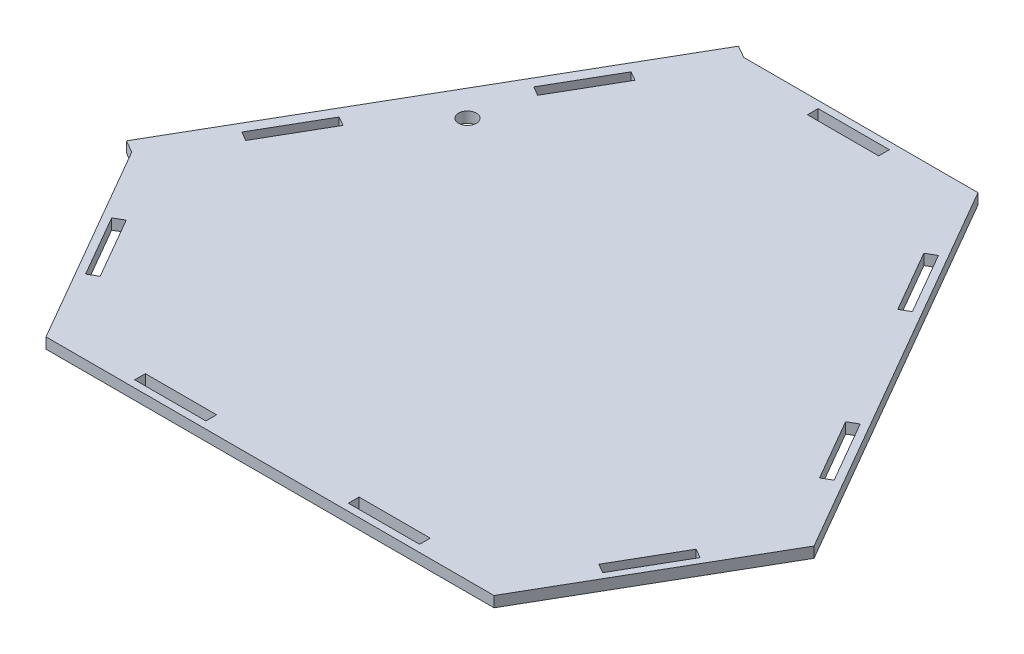
SolidWorks part; units mm, degrees
material "Acrylic (Medium-high impact)"
ref_plane "Front Plane" through (0, 0, 0) normal (0, 0, 1) x (1, 0, 0)
ref_plane "Top Plane" through (0, 0, 0) normal (0, 1, 0) x (1, 0, 0)
ref_plane "Right Plane" through (0, 0, 0) normal (1, 0, 0) x (0, 0, -1)
sketch "Sketch4" plane through (0, 0, 0) normal (0, 1, 0) x (1, 0, 0)
  line L0 (-30, 86.6025) -> (30, 86.6025)
  line L1 (0, 138.5641) -> (-120, -69.282) construction
  line L2 (-120, -69.282) -> (120, -69.282) construction
  line L3 (120, -69.282) -> (0, 138.5641) construction
  line L4 (-120, -69.282) -> (0, 0) construction
  line L5 (60, -69.282) -> (90, -17.3205)
  line L6 (0, 0) -> (0, 138.5641) construction
  line L7 (-60, -69.282) -> (-90, -17.3205)
  line L8 (-30, 86.6025) -> (-90, -17.3205)
  line L9 (-60, -69.282) -> (60, -69.282)
  line L10 (90, -17.3205) -> (30, 86.6025)
  line L11 (-32.8868, 91.6025) -> (32.8868, 91.6025)
  line L12 (95.7735, -17.3205) -> (32.8868, 91.6025)
  line L13 (62.8868, -74.282) -> (95.7735, -17.3205)
  line L14 (-62.8868, -74.282) -> (62.8868, -74.282)
  line L15 (-62.8868, -74.282) -> (-95.7735, -17.3205)
  line L16 (-32.8868, 91.6025) -> (-95.7735, -17.3205)
  line L17 (-94.3301, -14.8205) -> (-99.5263, -11.8205)
  line L18 (-94.3301, -14.8205) -> (-34.3058, 89.1447)
  line L19 (-99.5263, -11.8205) -> (-39.5019, 92.1447)
  line L20 (-34.3058, 89.1447) -> (-39.5019, 92.1447)
  line L21 (-92.5981, -15.8205) -> (-95.1962, -14.3205) construction
  circle A0 centre (0, 0) radius 69.282 construction
  dimension "D1" = 60
  dimension "D2" = 120
  dimension "D4" = 6
  dimension "D3" = 5
extrude "Boss-Extrude1" add sketch "Sketch4" against normal blind 3 contours L11 L12 L13 L14 L15 L16
sketch "Sketch5" plane through (0, 0, 0) normal (0, 1, 0) x (1, 0, 0)
  line L0 (-95.7735, -17.3205) -> (-32.8868, 91.6025)
  line L1 (-95.7735, -17.3205) -> (-99.2376, -15.3205)
  line L2 (-32.8868, 91.6025) -> (-36.3509, 93.6025)
  line L3 (-99.2376, -15.3205) -> (-36.3509, 93.6025)
  dimension "D1" = 4
extrude "Boss-Extrude2" add sketch "Sketch5" against normal through all
sketch "Sketch6" plane through (0, 0, 0) normal (0, 1, 0) x (1, 0, 0)
  line L0 (-67.7942, 39.141) -> (88.9811, -51.3732) construction
  line L1 (-36.3509, 93.6025) -> (-99.2376, -15.3205) construction
  circle A0 centre (-56.884, 38.0381) radius 2.5
  dimension "D1" = 5
  dimension "D2" = 10
  dimension "D3" = 4.5
extrude "Cut-Extrude1" cut sketch "Sketch6" against normal through all
sketch "Sketch7" plane through (0, 0, 0) normal (0, 1, 0) x (1, 0, 0)
  line L0 (-33.1171, 89.6025) -> (57.2276, 89.6025) construction
  line L1 (-70, 17.3205) -> (-80, 0) [skipped]
  line L2 (-32.8868, 91.6025) -> (32.8868, 91.6025) construction
  line L3 (-10, 89.6025) -> (10, 89.6025)
  line L4 (-10, 89.6025) -> (-10, 86.6025)
  line L5 (-10, 86.6025) -> (10, 86.6025)
  line L6 (10, 89.6025) -> (10, 86.6025)
  line L7 (0, 91.6025) -> (0, 31.1877) construction
  line L8 (-62.8868, -72.282) -> (98.3225, -72.282) construction
  line L9 (-62.8868, -74.282) -> (62.8868, -74.282) construction
  line L10 (-72.5981, 18.8205) -> (-82.5981, 1.5) [skipped]
  line L11 (-82.5981, 1.5) -> (-80, 0) [skipped]
  line L12 (-40, -72.282) -> (-20, -72.282)
  line L13 (-40, -72.282) -> (-40, -69.282)
  line L14 (-72.5981, 18.8205) -> (-70, 17.3205) [skipped]
  line L15 (-40, -69.282) -> (-20, -69.282)
  line L16 (-20, -72.282) -> (-20, -69.282)
  line L17 (20, -72.282) -> (40, -72.282)
  line L18 (20, -72.282) -> (20, -69.282)
  line L19 (20, -69.282) -> (40, -69.282)
  line L20 (40, -72.282) -> (40, -69.282)
  line L21 (-52.5981, 53.4615) -> (-50, 51.9615) [skipped]
  line L22 (-42.5981, 70.782) -> (-40, 69.282) [skipped]
  line L23 (-40, 69.282) -> (-50, 51.9615) [skipped]
  line L24 (-42.5981, 70.782) -> (-52.5981, 53.4615) [skipped]
  line L25 (50, 51.9615) -> (40, 69.282)
  line L26 (52.5981, 53.4615) -> (42.5981, 70.782)
  line L27 (42.5981, 70.782) -> (40, 69.282)
  line L28 (52.5981, 53.4615) -> (50, 51.9615)
  line L29 (72.5981, 18.8205) -> (70, 17.3205)
  line L30 (82.5981, 1.5) -> (80, 0)
  line L31 (80, 0) -> (70, 17.3205)
  line L32 (82.5981, 1.5) -> (72.5981, 18.8205)
  line L33 (80, -34.641) -> (70, -51.9615)
  line L34 (82.5981, -36.141) -> (72.5981, -53.4615)
  line L35 (72.5981, -53.4615) -> (70, -51.9615)
  line L36 (82.5981, -36.141) -> (80, -34.641)
  line L37 (-70, -51.9615) -> (-80, -34.641)
  line L38 (-72.5981, -53.4615) -> (-82.5981, -36.141)
  line L39 (-82.5981, -36.141) -> (-80, -34.641)
  line L40 (-72.5981, -53.4615) -> (-70, -51.9615)
  line L41 (-36.3509, 93.6025) -> (-99.2376, -15.3205) construction
  line L42 (-36.3509, 93.6025) -> (-33.7528, 92.1025) construction
  line L43 (-99.2376, -15.3205) -> (-96.6395, -16.8205) construction
  line L44 (-33.7528, 92.1025) -> (-96.6395, -16.8205) construction
  line L45 (-45.1962, 72.282) -> (-55.1962, 54.9615)
  line L46 (-45.1962, 72.282) -> (-42.5981, 70.782)
  line L47 (-55.1962, 54.9615) -> (-52.5981, 53.4615)
  line L48 (-42.5981, 70.782) -> (-52.5981, 53.4615)
  line L49 (-75.1962, 20.3205) -> (-85.1962, 3)
  line L50 (-75.1962, 20.3205) -> (-72.5981, 18.8205)
  line L51 (-85.1962, 3) -> (-82.5981, 1.5)
  line L52 (-72.5981, 18.8205) -> (-82.5981, 1.5)
  line L53 (0, -74.282) -> (0, -25.4234) construction
  line L54 (-67.7942, 39.141) -> (-18.2487, 10.5359) construction
  circle A0 centre (0, 0) radius 16.4887 construction
  point P46 (0, 0)
  point P55 (0, 0)
  dimension "D1" = 2
  dimension "D2" = 20
  dimension "D3" = 3
  dimension "D4" = 2
  dimension "D5" = 10
  dimension "D6" = 3
  dimension "D7" = 20
  dimension "D8" = 20
  dimension "D9" = 3
  dimension "D10" = 40
  dimension "D11" = 20
  dimension "D14" = 3
  dimension "D15" = 3
  dimension "D16" = 3
  dimension "D17" = 40
  dimension "D18" = 20
  dimension "D19" = 20
  dimension "D20" = 20
  dimension "D12" = 3
  dimension "D13" = 3
extrude "Cut-Extrude2" cut sketch "Sketch7" against normal through all
